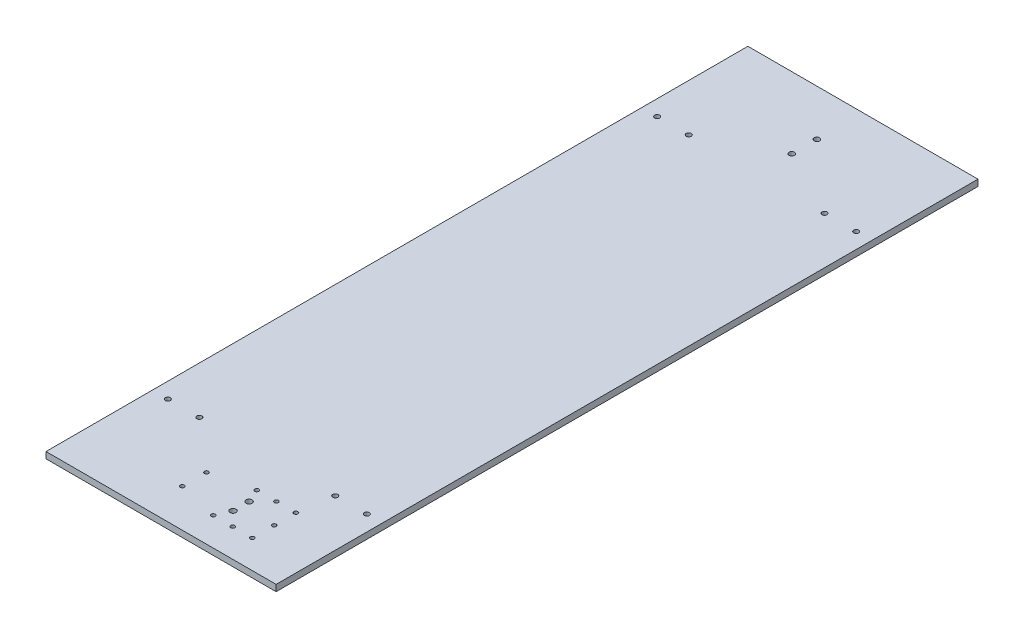
SolidWorks part; units mm, degrees
material "Pin"
ref_plane "Plan de face" through (0, 0, 0) normal (0, 0, 1) x (1, 0, 0)
ref_plane "Plan de dessus" through (0, 0, 0) normal (0, 1, 0) x (1, 0, 0)
ref_plane "Plan de droite" through (0, 0, 0) normal (1, 0, 0) x (0, 0, -1)
sketch "Esquisse1" plane through (0, 0, 0) normal (0, 1, 0) x (1, 0, 0)
  line L1 (114.75, 350) -> (-114.75, 350)
  line L2 (114.75, 350) -> (114.75, -350)
  line L3 (114.75, -350) -> (-114.75, -350)
  line L4 (-114.75, 350) -> (-114.75, -350)
  line L5 (114.75, 350) -> (-114.75, -350) construction
  line L6 (114.75, -350) -> (-114.75, 350) construction
  point P0 (0, 0)
  dimension "D1" = 229.5
  dimension "D2" = 700
extrude "Boss.-Extru.1" add sketch "Esquisse1" along normal blind 6.35
sketch "Esquisse2" plane through (0, 0, 0) normal (0, -1, 0) x (1, 0, 0)
  line L0 (3.4925, 0) -> (-3.4925, 0) construction
  line L1 (0, -3.4925) -> (0, 3.4925) construction
  circle A0 centre (-16.75, 312) radius 2
  circle A1 centre (-16.75, 288) radius 2
  circle A2 centre (23.75, 321.75) radius 2
  circle A3 centre (23.75, 278.25) radius 2
  circle A4 centre (43.25, 278.25) radius 2
  circle A5 centre (43.25, 321.75) radius 2
  circle A6 centre (62.75, 321.75) radius 2
  circle A7 centre (62.75, 300) radius 2
  circle A8 centre (62.75, 278.25) radius 2
  circle A9 centre (29.75, 292) radius 3
  circle A10 centre (29.75, 308) radius 3
  circle A11 centre (67.75, 244) radius 2.5
  circle A12 centre (99.25, 244) radius 2.5
  circle A13 centre (67.75, -244) radius 2.5
  circle A14 centre (99.25, -244) radius 2.5
  circle A15 centre (-99.25, -244) radius 2.5
  circle A16 centre (-67.75, -244) radius 2.5
  circle A17 centre (-99.25, 244) radius 2.5
  circle A18 centre (-67.75, 244) radius 2.5
extrude "Enlèv. mat.-Extru.1" cut sketch "Esquisse2" against normal through all
sketch "Esquisse3" plane through (0, 6.35, 0) normal (0, 1, 0) x (1, 0, 0)
  circle A0 centre (0, 279) radius 2.75
  circle A1 centre (0, 304) radius 2.75
  circle A2 centre (67.75, 244) radius 2.5 construction
  dimension "D2" = 5.5
  dimension "D1" = 25
  dimension "D3" = 35
extrude "Enlèv. mat.-Extru.2" cut sketch "Esquisse3" against normal through all
